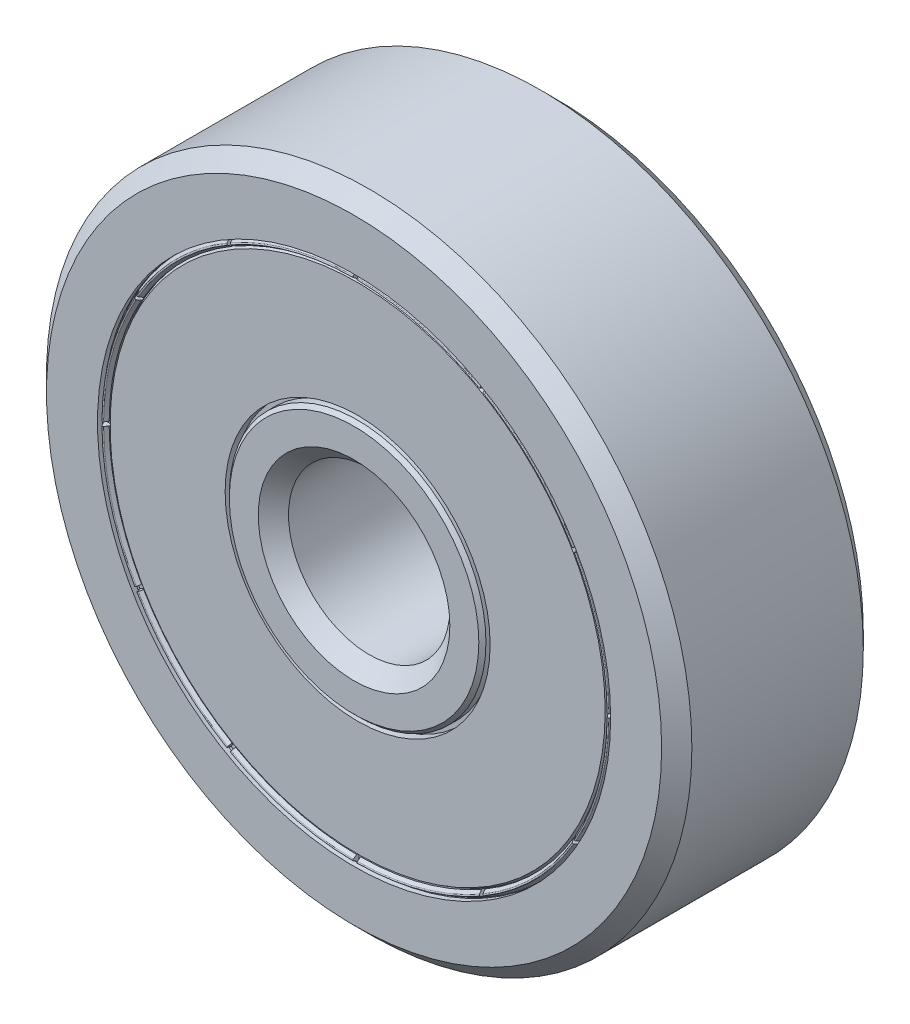
SolidWorks part; units mm, degrees
ref_plane "Front Plane" through (0, 0, 0) normal (0, 0, 1) x (1, 0, 0)
ref_plane "Top Plane" through (0, 0, 0) normal (0, 1, 0) x (1, 0, 0)
ref_plane "Right Plane" through (0, 0, 0) normal (1, 0, 0) x (0, 0, -1)
sketch "Sketch1" plane through (0, 0, 0) normal (0, 0, 1) x (1, 0, 0)
  circle A0 centre (0, 0) radius 2
  circle A1 centre (0, 0) radius 8
  dimension "OD" = 16
  dimension "ID" = 4
sketch "Sketch2" plane through (0, 0, 0) normal (1, 0, 0) x (0, 0, -1)
  line L0 (-2.5, 8) -> (2.5, 8)
  line L1 (-2.5, 2) -> (-2.5, -2) construction
  line L2 (2.5, 8) -> (2.5, -8) construction
  line L3 (-2.5, 0) -> (2.5, 0) construction
  line L6 (0, 8) -> (0, 2) construction
  circle A0 centre (0, 5) radius 2.1 construction
  point P8 (0, 8)
  dimension "Approx. Ball Dia." = 4.2
  dimension "Width" = 5
  dimension "For Shaft Diameter" = 4
  dimension "For Housing ID" = 16
sketch "Sketch3" plane through (0, 0, 0) normal (1, 0, 0) x (0, 0, -1)
  line L0 (0, 0) -> (0, 4) construction
  line L1 (-2.5, 2) -> (-2.5, -2) construction
  line L2 (2.125, 8) -> (-2.125, 8)
  line L3 (-2.125, 8) -> (-2.5, 7.625)
  line L4 (-2.5, 7.625) -> (-2.5, 6.3605)
  line L5 (-2.5, 6.3605) -> (-2.375, 6.3605)
  line L6 (-2.375, 6.3605) -> (-2.375, 6.7303)
  line L7 (-2.375, 6.7303) -> (-2.2866, 6.8187)
  line L8 (-2.2866, 6.8187) -> (-1.05, 6.8187)
  line L10 (-2.5, 8) -> (2.5, 8) construction
  line L12 (-2.375, 6.7303) -> (-2.375, 7.1) construction
  line L13 (2.2866, 6.8187) -> (1.05, 6.8187)
  line L14 (2.375, 6.7303) -> (2.2866, 6.8187)
  line L15 (2.375, 6.3605) -> (2.375, 6.7303)
  line L16 (2.5, 6.3605) -> (2.375, 6.3605)
  line L17 (2.5, 7.625) -> (2.5, 6.3605)
  line L18 (2.125, 8) -> (2.5, 7.625)
  line L19 (2.125, 2) -> (-2.125, 2)
  line L20 (-2.125, 2) -> (-2.5, 2.375)
  line L21 (-2.5, 2.375) -> (-2.5, 3.093)
  line L22 (-2.5, 3.093) -> (-2.4116, 3.1813)
  line L23 (-2.4116, 3.1813) -> (-1.05, 3.1813)
  line L25 (2.4116, 3.1813) -> (1.05, 3.1813)
  line L26 (2.5, 3.093) -> (2.4116, 3.1813)
  line L27 (2.5, 2.375) -> (2.5, 3.093)
  line L28 (2.125, 2) -> (2.5, 2.375)
  circle A2 centre (0, 5) radius 2.1 construction
  arc A3 (-1.05, 6.8187) -> (1.05, 6.8187) centre (0, 5) cw
  arc A4 (-1.05, 3.1813) -> (1.05, 3.1813) centre (0, 5) ccw
  point P5 (0, 7.1)
  point P31 (0, 8)
  point P37 (0, 2)
  dimension "D1" = 45
  dimension "D2" = 0.125
  dimension "D3" = 2.1
  dimension "D4" = 0.375
revolve "Revolve1" add sketch "Sketch3" angle 360 about L3
sketch "Sketch4" plane through (0, 0, 0) normal (1, 0, 0) x (0, 0, -1)
  line L0 (0, 7.1) -> (0, 2.9)
  line L1 (0, 8) -> (0, 2) construction
  circle A0 centre (0, 5) radius 2.1 construction
  arc A1 (0, 2.9) -> (0, 7.1) centre (0, 5) cw
revolve "Revolve2" add sketch "Sketch4" angle 360 about L6
pattern_circular "CirPattern1" count 6 over 360 about axis through (0, 0, 0) along (0, 0, 1) of bodies 106
sketch "Sketch5" plane through (0, 0, 0) normal (1, 0, 0) x (0, 0, -1)
  line L0 (-2.1, 5) -> (-2.1, 3.1813) construction
  line L1 (-2.4116, 3.1813) -> (-1.05, 3.1813) construction
  line L3 (-2.1, 3.1813) -> (-2.2039, 3.1813)
  line L4 (-2.2039, 3.1813) -> (-2.2039, 3.2852)
  line L5 (-2.2039, 3.2852) -> (-2.4116, 3.2852)
  line L6 (-2.4116, 3.2852) -> (-2.4116, 6.1367)
  line L7 (-2.4116, 6.1367) -> (-2.2039, 6.2567)
  line L8 (-2.2039, 6.2567) -> (-2.1, 6.2567)
  line L9 (-2.1, 6.2567) -> (-2.1, 3.1813)
  line L10 (0, 5) -> (0, 8) construction
  line L11 (2.2039, 6.2567) -> (2.1, 6.2567)
  line L12 (2.4116, 6.1367) -> (2.2039, 6.2567)
  line L13 (2.4116, 3.2852) -> (2.4116, 6.1367)
  line L14 (2.2039, 3.2852) -> (2.4116, 3.2852)
  line L15 (2.2039, 3.1813) -> (2.2039, 3.2852)
  line L16 (2.1, 3.1813) -> (2.2039, 3.1813)
  line L17 (2.1, 6.2567) -> (2.1, 3.1813)
  line L18 (-2.4116, 6.1367) -> (-2.3077, 6.1367) construction
  line L19 (-2.3077, 6.1367) -> (-2.2039, 6.1367) construction
  line L20 (-2.2039, 6.1367) -> (-2.1, 6.1367) construction
  line L21 (-2.2039, 6.2567) -> (-2.2039, 6.3605) construction
  circle A0 centre (0, 5) radius 2.1 construction
  dimension "D1" = 30
revolve "Revolve3" add sketch "Sketch5" angle 360 about L3
sketch "Sketch6" plane through (0, 0, 0) normal (1, 0, 0) x (0, 0, -1)
  line L0 (-2.312, 6.3605) -> (-2.3338, 6.3605)
  line L1 (-2.3338, 6.3605) -> (-2.5, 6.2645)
  line L2 (-2.5, 6.2645) -> (-2.387, 6.1854)
  line L4 (-2.4116, 6.1367) -> (-2.2039, 6.2567) construction
  line L5 (-2.312, 6.1942) -> (-2.312, 6.3605)
  line L6 (-2.5, 6.3605) -> (-2.375, 6.3605) construction
  line L7 (-2.387, 6.1854) -> (-2.362, 6.1854)
  line L8 (-2.362, 6.1854) -> (-2.312, 6.1942)
  line L9 (-2.5, 7.625) -> (-2.5, -7.625) construction
  line L11 (-2.362, 6.1854) -> (-2.337, 6.1854) construction
  line L12 (-2.337, 6.1854) -> (-2.312, 6.1854) construction
  point P27 (-2.3229, 6.3605)
  dimension "D1" = 30
  dimension "D3" = 10
  dimension "D2" = 35
  dimension "D4" = 0.025
  dimension "D5" = 0.1663
revolve "Revolve4" add sketch "Sketch6" angle 360 about L3
fillet "Fillet1" radius 0.025 1 edges at (6.2645, 0, 2.5)
sketch "Sketch7" plane through (0, 0, 0) normal (0, 0, 1) x (1, 0, 0)
  line L0 (-0.05, 6.3605) -> (-0.05, 6.4605)
  line L1 (-0.05, 6.3605) -> (0.05, 6.3605) construction
  line L2 (-0.05, 6.3605) -> (-0.05, 6.1854)
  line L3 (-0.05, 6.1854) -> (0.05, 6.1854) construction
  line L4 (0.05, 6.3605) -> (0.05, 6.1854)
  line L5 (-0.05, 6.4605) -> (0.05, 6.4605)
  line L6 (0.05, 6.4605) -> (0.05, 6.3605)
  line L7 (-0.05, 6.1854) -> (-0.05, 6.0854)
  line L8 (-0.05, 6.0854) -> (0.05, 6.0854)
  line L9 (0.05, 6.0854) -> (0.05, 6.1854)
  dimension "D1" = 0.1
extrude "Cut-Extrude1" cut sketch "Sketch7" along normal through all from vertex at 2.3229 starting at point (0, 6.3605, 2.3229)
pattern_circular "CirPattern2" count 12 over 360 about axis through (0, 0, 2.5) along (0, 0, -1) of "Cut-Extrude1"
mirror "Mirror1" about plane through (0, 0, 0) normal (0, 0, 1) of bodies 120
equation "\"Approx. Ball Dia.@Sketch2\"=( \"OD@Sketch1\" - \"ID@Sketch1\" )  * .5 * .7"
equation "\"D2@Sketch3\"=\"Width@Sketch2\"*.025"
equation "\"D3@Sketch3\"=\"Approx. Ball Dia.@Sketch2\"*.5"
equation "\"D4@Sketch3\"=\"Width@Sketch2\"*.075"
equation "\"Approx No of Balls\"= ( pi * \"OD@Sketch1\" ) * .5 / \"Approx. Ball Dia.@Sketch2\""
equation "\"D1@CirPattern1\"=\"Approx No of Balls\""
equation "\"D4@Sketch6\"=\"D2@Sketch3\"*.2"
equation "\"D1@CirPattern2\"=\"Approx No of Balls\"*2"
equation "\"D5@Sketch6\"=\"D2@Sketch3\"*1.33"
equation "\"D1@Fillet1\"=\"d4@sketch6\""
